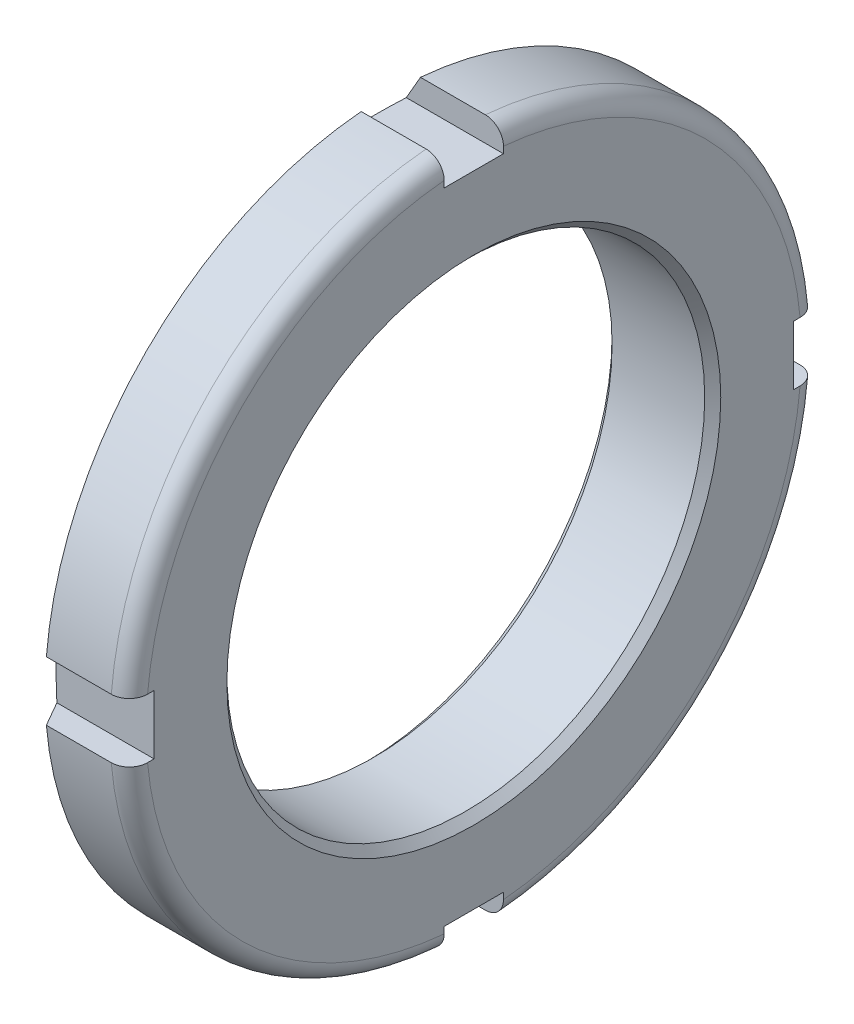
SolidWorks part; units mm, degrees
ref_plane "Front Plane" through (0, 0, 0) normal (0, 0, 1) x (1, 0, 0)
ref_plane "Top Plane" through (0, 0, 0) normal (0, 1, 0) x (1, 0, 0)
ref_plane "Right Plane" through (0, 0, 0) normal (1, 0, 0) x (0, 0, -1)
ref_plane "Plane1" through (0, 0, 0) normal (-1, 0, 0) x (0, -1, 0)
sketch "Sketch1" plane through (0, 0, 0) normal (-1, 0, 0) x (0, -1, 0)
  circle A0 centre (0, 0) radius 24.188
  circle A1 centre (0, 0) radius 35
extrude "Boss-Extrude1" add sketch "Sketch1" against normal blind 11
chamfer "Chamfer1" distance 4.5 angle 30 1 edges at (0, 0, -35)
sketch "Sketch2" plane through (11, 0, 0) normal (1, 0, 0) x (0, 0, -1)
  line L0 (34.8712, 3) -> (32.3712, 3)
  line L1 (32.3712, 3) -> (32.3712, -3)
  line L2 (32.3712, -3) -> (34.8712, -3)
  arc A0 (34.8712, -3) -> (34.8712, 3) centre (0, 0) ccw
extrude "Cut-Extrude1" cut sketch "Sketch2" against normal up to next
sketch "Sketch3" plane through (11, 0, 0) normal (1, 0, 0) x (0, 0, -1)
  line L0 (3, -34.8712) -> (3, -32.3712)
  line L1 (3, -32.3712) -> (-3, -32.3712)
  line L2 (-3, -32.3712) -> (-3, -34.8712)
  arc A0 (-3, -34.8712) -> (3, -34.8712) centre (0, 0) ccw
extrude "Cut-Extrude2" cut sketch "Sketch3" against normal up to next
sketch "Sketch4" plane through (11, 0, 0) normal (1, 0, 0) x (0, 0, -1)
  line L0 (-34.8712, -3) -> (-32.3712, -3)
  line L1 (-32.3712, -3) -> (-32.3712, 3)
  line L2 (-32.3712, 3) -> (-34.8712, 3)
  arc A0 (-34.8712, 3) -> (-34.8712, -3) centre (0, 0) ccw
extrude "Cut-Extrude3" cut sketch "Sketch4" against normal up to next
sketch "Sketch5" plane through (11, 0, 0) normal (1, 0, 0) x (0, 0, -1)
  line L0 (-3, 34.8712) -> (-3, 32.3712)
  line L1 (-3, 32.3712) -> (3, 32.3712)
  line L2 (3, 32.3712) -> (3, 34.8712)
  arc A0 (3, 34.8712) -> (-3, 34.8712) centre (0, 0) ccw
extrude "Cut-Extrude4" cut sketch "Sketch5" against normal up to next
chamfer "Chamfer2" distance 0.812 angle 45 1 edges at (0, 0, -24.188)
chamfer "Chamfer3" distance 0.812 angle 45 1 edges at (11, 0, -24.188)
fillet "Fillet1" radius 1.8333 3 edges at (11, -24.7487, -24.7487) (11, 24.7487, 24.7487) (11, -24.7487, 24.7487)
fillet "Fillet2" radius 1.8333 1 edges at (11, 24.7487, -24.7487)
